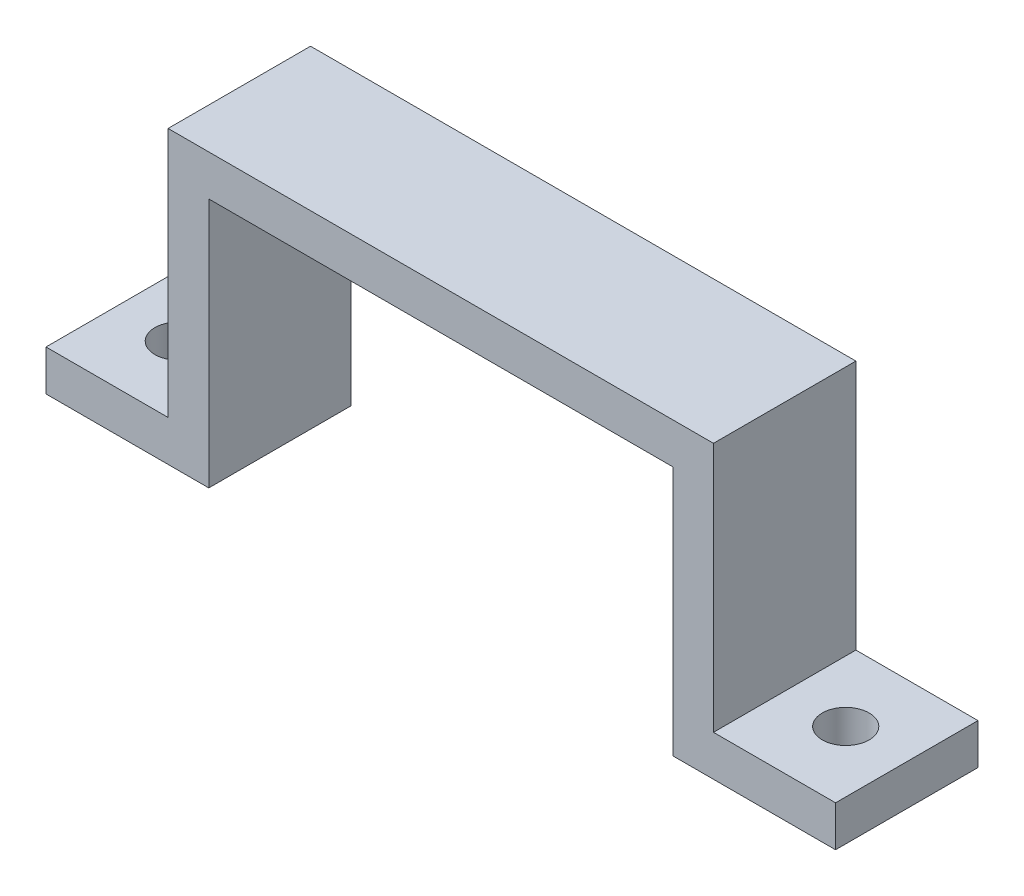
SolidWorks part; units mm, degrees
ref_plane "Front Plane" through (0, 0, 0) normal (0, 0, 1) x (1, 0, 0)
ref_plane "Top Plane" through (0, 0, 0) normal (0, 1, 0) x (1, 0, 0)
ref_plane "Right Plane" through (0, 0, 0) normal (1, 0, 0) x (0, 0, -1)
sketch "Sketch1" plane through (0, 0, 0) normal (0, 0, 1) x (1, 0, 0)
  line L0 (0, 0) -> (8, 0)
  line L1 (8, 0) -> (8, 12.3)
  line L2 (8, 12.3) -> (30.8, 12.3)
  line L3 (30.8, 12.3) -> (30.8, 0)
  line L4 (30.8, 0) -> (38.8, 0)
  line L5 (38.8, 0) -> (38.8, 2)
  line L6 (38.8, 2) -> (32.8, 2)
  line L7 (32.8, 2) -> (32.8, 14.3)
  line L8 (32.8, 14.3) -> (6, 14.3)
  line L9 (6, 14.3) -> (6, 2)
  line L10 (6, 2) -> (0, 2)
  line L11 (0, 2) -> (0, 0)
  dimension "D1" = 22.8
  dimension "D2" = 2
  dimension "D3" = 2
  dimension "D4" = 2
  dimension "D5" = 2
  dimension "D6" = 2
  dimension "D7" = 8
  dimension "D8" = 8
  dimension "D9" = 12.3
extrude "Boss-Extrude1" add sketch "Sketch1" along normal blind 7
sketch "Sketch2" plane through (0, 2, 0) normal (0, 1, 0) x (1, 0, 0)
  line L0 (32.8, 0) -> (38.8, -7)
  line L1 (38.8, 0) -> (32.8, -7)
  line L2 (0, 0) -> (6, -7)
  line L3 (6, 0) -> (0, -7)
  circle A0 centre (35.8, -3.5) radius 1.15
  circle A1 centre (3, -3.5) radius 1.15
extrude "Cut-Extrude1" cut sketch "Sketch2" against normal blind 7 contours A1 | A0
